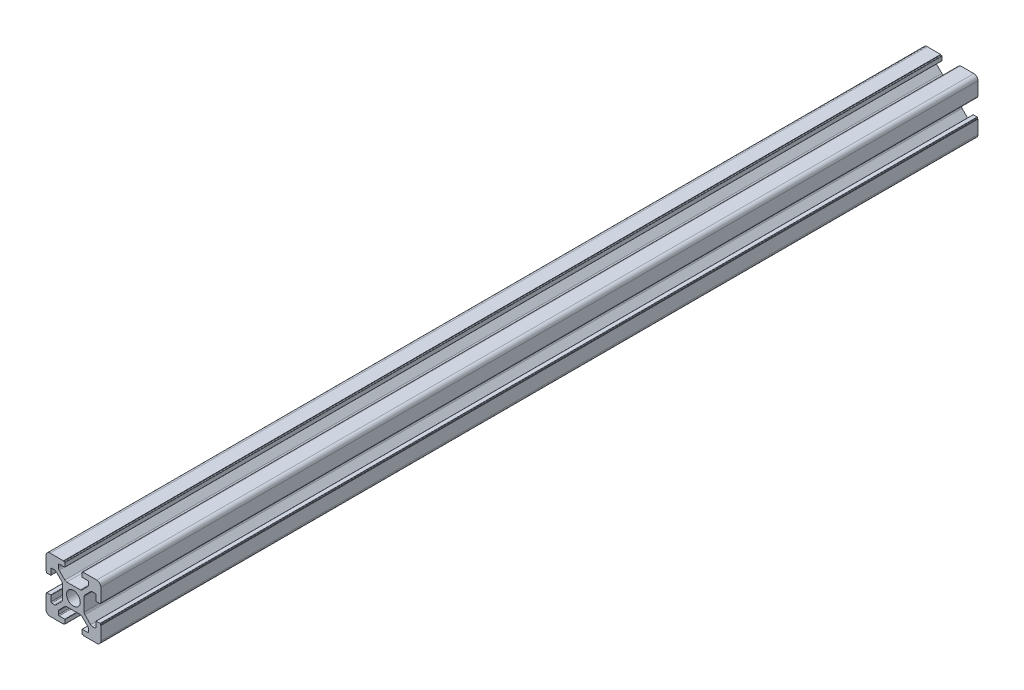
SolidWorks part; units mm, degrees
material "6063-T5"
ref_plane "前视基准面" through (0, 0, 0) normal (0, 0, 1) x (1, 0, 0)
ref_plane "上视基准面" through (0, 0, 0) normal (0, 1, 0) x (1, 0, 0)
ref_plane "右视基准面" through (0, 0, 0) normal (1, 0, 0) x (0, 0, -1)
sketch "草图1" plane through (0, 0, 0) normal (0, 0, 1) x (1, 0, 0)
  line L0 (-1.4389, 10) -> (24.3741, 10) construction
  line L1 (20, 13.6) -> (20, 20)
  line L2 (0, 0) -> (0, 6.4)
  line L3 (0, 20) -> (6.4, 20)
  line L4 (20, 0) -> (20, 6.4)
  line L5 (10, 21.5388) -> (10, -2.4017) construction
  line L6 (6.9, 18.3) -> (6.9, 19.7)
  line L7 (6.8, 18.2) -> (4.8, 18.2)
  line L8 (4.5, 17.9) -> (4.5, 16.9749)
  line L9 (4.7929, 16.2678) -> (6.8678, 14.1929)
  line L10 (7.5749, 13.9) -> (12.4251, 13.9)
  line L11 (6.8, 19.8) -> (6.4, 19.8)
  line L12 (6.4, 19.8) -> (6.4, 20)
  line L13 (0, 13.6) -> (0.2, 13.6)
  line L14 (0.2, 13.6) -> (0.2, 13.2)
  line L15 (0.3, 13.1) -> (1.7, 13.1)
  line L16 (1.8, 13.2) -> (1.8, 15.2)
  line L17 (2.1, 15.5) -> (3.0251, 15.5)
  line L18 (3.7322, 15.2071) -> (5.8071, 13.1322)
  line L19 (6.1, 12.4251) -> (6.1, 7.5749)
  line L20 (13.6, 19.8) -> (13.6, 20)
  line L21 (13.2, 19.8) -> (13.6, 19.8)
  line L22 (13.1, 18.3) -> (13.1, 19.7)
  line L23 (13.2, 18.2) -> (15.2, 18.2)
  line L24 (15.5, 17.9) -> (15.5, 16.9749)
  line L25 (15.2071, 16.2678) -> (13.1322, 14.1929)
  line L26 (0, 6.4) -> (0.2, 6.4)
  line L27 (0.2, 6.4) -> (0.2, 6.8)
  line L28 (0.3, 6.9) -> (1.7, 6.9)
  line L29 (1.8, 6.8) -> (1.8, 4.8)
  line L30 (2.1, 4.5) -> (3.0251, 4.5)
  line L31 (3.7322, 4.7929) -> (5.8071, 6.8678)
  line L32 (13.6, 20) -> (20, 20)
  line L33 (0, 13.6) -> (0, 20)
  line L34 (13.6, 0.2) -> (13.6, 0)
  line L35 (13.2, 0.2) -> (13.6, 0.2)
  line L36 (13.1, 1.7) -> (13.1, 0.3)
  line L37 (13.2, 1.8) -> (15.2, 1.8)
  line L38 (15.5, 2.1) -> (15.5, 3.0251)
  line L39 (15.2071, 3.7322) -> (13.1322, 5.8071)
  line L40 (4.5, 2.1) -> (4.5, 3.0251)
  line L41 (6.8, 1.8) -> (4.8, 1.8)
  line L42 (6.4, 0.2) -> (6.4, 0)
  line L43 (6.8, 0.2) -> (6.4, 0.2)
  line L44 (6.9, 1.7) -> (6.9, 0.3)
  line L45 (4.7929, 3.7322) -> (6.8678, 5.8071)
  line L46 (7.5749, 6.1) -> (12.4251, 6.1)
  line L47 (20, 6.4) -> (19.8, 6.4)
  line L48 (19.8, 6.4) -> (19.8, 6.8)
  line L49 (19.7, 6.9) -> (18.3, 6.9)
  line L50 (18.2, 6.8) -> (18.2, 4.8)
  line L51 (17.9, 4.5) -> (16.9749, 4.5)
  line L52 (16.2678, 4.7929) -> (14.1929, 6.8678)
  line L53 (13.9, 12.4251) -> (13.9, 7.5749)
  line L54 (16.2678, 15.2071) -> (14.1929, 13.1322)
  line L55 (17.9, 15.5) -> (16.9749, 15.5)
  line L56 (18.2, 13.2) -> (18.2, 15.2)
  line L57 (19.7, 13.1) -> (18.3, 13.1)
  line L58 (19.8, 13.6) -> (19.8, 13.2)
  line L59 (20, 13.6) -> (19.8, 13.6)
  line L60 (0, 0) -> (6.4, 0)
  line L61 (13.6, 0) -> (20, 0)
  arc A0 (6.1, 12.4251) -> (5.8071, 13.1322) centre (5.1, 12.4251) ccw
  arc A1 (7.5749, 13.9) -> (6.8678, 14.1929) centre (7.5749, 14.9) cw
  arc A2 (4.5, 16.9749) -> (4.7929, 16.2678) centre (5.5, 16.9749) ccw
  arc A3 (3.7322, 15.2071) -> (3.0251, 15.5) centre (3.0251, 14.5) ccw
  arc A4 (4.5, 17.9) -> (4.8, 18.2) centre (4.8, 17.9) cw
  arc A5 (1.8, 15.2) -> (2.1, 15.5) centre (2.1, 15.2) cw
  arc A6 (0.3, 13.1) -> (0.2, 13.2) centre (0.3, 13.2) cw
  arc A7 (6.9, 19.7) -> (6.8, 19.8) centre (6.8, 19.7) ccw
  arc A8 (1.7, 13.1) -> (1.8, 13.2) centre (1.7, 13.2) ccw
  arc A9 (6.9, 18.3) -> (6.8, 18.2) centre (6.8, 18.3) cw
  arc A10 (13.1, 19.7) -> (13.2, 19.8) centre (13.2, 19.7) cw
  arc A11 (13.1, 18.3) -> (13.2, 18.2) centre (13.2, 18.3) ccw
  arc A12 (15.5, 17.9) -> (15.2, 18.2) centre (15.2, 17.9) ccw
  arc A13 (15.5, 16.9749) -> (15.2071, 16.2678) centre (14.5, 16.9749) cw
  arc A14 (12.4251, 13.9) -> (13.1322, 14.1929) centre (12.4251, 14.9) ccw
  arc A15 (0.3, 6.9) -> (0.2, 6.8) centre (0.3, 6.8) ccw
  arc A16 (1.7, 6.9) -> (1.8, 6.8) centre (1.7, 6.8) cw
  arc A17 (1.8, 4.8) -> (2.1, 4.5) centre (2.1, 4.8) ccw
  arc A18 (3.7322, 4.7929) -> (3.0251, 4.5) centre (3.0251, 5.5) cw
  arc A19 (6.1, 7.5749) -> (5.8071, 6.8678) centre (5.1, 7.5749) cw
  arc A20 (13.1, 0.3) -> (13.2, 0.2) centre (13.2, 0.3) ccw
  arc A21 (13.1, 1.7) -> (13.2, 1.8) centre (13.2, 1.7) cw
  arc A22 (15.5, 2.1) -> (15.2, 1.8) centre (15.2, 2.1) cw
  arc A23 (15.5, 3.0251) -> (15.2071, 3.7322) centre (14.5, 3.0251) ccw
  arc A24 (12.4251, 6.1) -> (13.1322, 5.8071) centre (12.4251, 5.1) cw
  arc A25 (4.5, 2.1) -> (4.8, 1.8) centre (4.8, 2.1) ccw
  arc A26 (6.9, 0.3) -> (6.8, 0.2) centre (6.8, 0.3) cw
  arc A27 (6.9, 1.7) -> (6.8, 1.8) centre (6.8, 1.7) ccw
  arc A28 (4.5, 3.0251) -> (4.7929, 3.7322) centre (5.5, 3.0251) cw
  arc A29 (7.5749, 6.1) -> (6.8678, 5.8071) centre (7.5749, 5.1) ccw
  arc A30 (19.7, 6.9) -> (19.8, 6.8) centre (19.7, 6.8) cw
  arc A31 (18.3, 6.9) -> (18.2, 6.8) centre (18.3, 6.8) ccw
  arc A32 (18.2, 4.8) -> (17.9, 4.5) centre (17.9, 4.8) cw
  arc A33 (16.2678, 4.7929) -> (16.9749, 4.5) centre (16.9749, 5.5) ccw
  arc A34 (13.9, 7.5749) -> (14.1929, 6.8678) centre (14.9, 7.5749) ccw
  arc A35 (13.9, 12.4251) -> (14.1929, 13.1322) centre (14.9, 12.4251) cw
  arc A36 (16.2678, 15.2071) -> (16.9749, 15.5) centre (16.9749, 14.5) cw
  arc A37 (18.2, 15.2) -> (17.9, 15.5) centre (17.9, 15.2) ccw
  arc A38 (18.3, 13.1) -> (18.2, 13.2) centre (18.3, 13.2) cw
  arc A39 (19.7, 13.1) -> (19.8, 13.2) centre (19.7, 13.2) ccw
  circle A40 centre (10, 10) radius 2.5
  point P39 (0.2, 13.1)
  point P42 (6.9, 19.8)
  point P45 (1.8, 13.1)
  point P48 (6.9, 18.2)
  point P66 (10, 13.9)
  point P83 (6.1, 10)
  dimension "D19" = 1
  dimension "D20" = 1
  dimension "D21" = 0.3
  dimension "D22" = 0.1
  dimension "D23" = 5
  dimension "D1" = 20
  dimension "D2" = 20
  dimension "D3" = 10
  dimension "D4" = 10
  dimension "D5" = 1.8
  dimension "D6" = 0.5
  dimension "D7" = 1.6
  dimension "D8" = 3.1
  dimension "D9" = 6.1
  dimension "D10" = 5.5
  dimension "D11" = 3.1
  dimension "D12" = 6.1
  dimension "D13" = 5.5
  dimension "D14" = 1.8
  dimension "D15" = 0.5
  dimension "D16" = 1.5
  dimension "D17" = 45
  dimension "D18" = 1.6
extrude "凸台-拉伸1" add sketch "草图1" along normal blind 320
fillet "圆角1" radius 1.5 4 edges at (20, 0, 160) (0, 0, 160) (0, 20, 160) (20, 20, 160)
